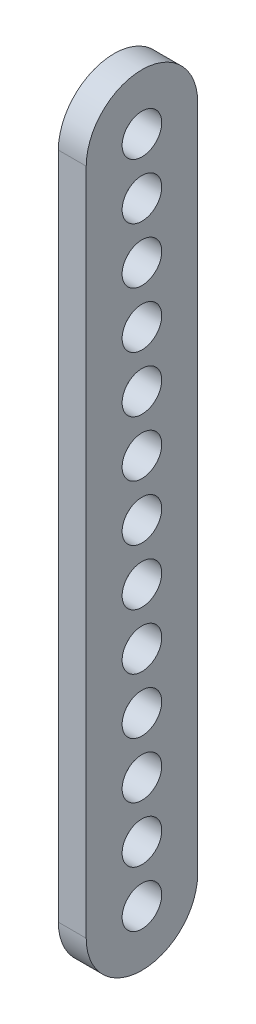
SolidWorks part; units mm, degrees
ref_plane "Front Plane" through (0, 0, 0) normal (0, 0, 1) x (1, 0, 0)
ref_plane "Top Plane" through (0, 0, 0) normal (0, 1, 0) x (1, 0, 0)
ref_plane "Right Plane" through (0, 0, 0) normal (1, 0, 0) x (0, 0, -1)
sketch "Sketch1" plane through (0, 0, 0) normal (1, 0, 0) x (0, 0, -1)
  line L0 (0, 30) -> (0, -30) construction
  line L1 (5, 30) -> (5, -30)
  line L2 (-5, 30) -> (-5, -30)
  arc A0 (5, 30) -> (-5, 30) centre (0, 30) ccw
  arc A1 (-5, -30) -> (5, -30) centre (0, -30) ccw
  point P2 (0, 0)
  point P7 (0, 0)
  dimension "D1" = 10
  dimension "D2" = 60
extrude "Boss-Extrude1" add sketch "Sketch1" along normal blind 2.5
hole_wizard "5/32 (0.14) Diameter Hole1" positions "Sketch5" profile "Sketch6" hole size "5/32" standard "ANSI Inch" end condition through all
sketch "Sketch5" plane through (2.5, 0, 0) normal (1, 0, 0) x (0, 0, -1)
  point P0 (0, 0)
sketch "Sketch6" plane through (2.5, 0, 0) normal (0, 1, 0) x (0, 0, -1)
  line L0 (0, 0) -> (0, 2.5)
  line L1 (0, 2.5) -> (1.778, 2.5)
  line L2 (1.778, 2.5) -> (1.778, 0)
  line L5 (1.778, 0) -> (0, 0)
  line L11 (0, -6.35) -> (0, 107.95) construction
  dimension "Thru Hole Dia." = 3.556
  dimension "Thru Hole Depth" = 2.5
pattern_linear "LPattern1" count 7 spacing 5 along (0, 1, 0) of "5/32 (0.14) Diameter Hole1"
mirror "Mirror1" about plane through (0, 0, 0) normal (0, 1, 0) of "LPattern1"
